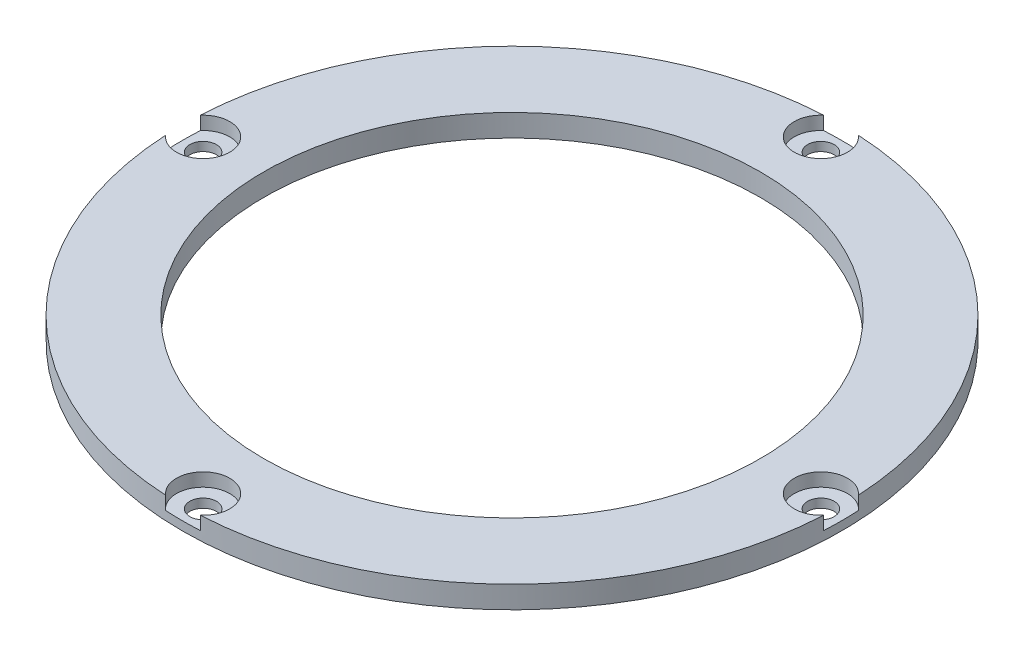
SolidWorks part; units mm, degrees
ref_plane "前视基准面" through (0, 0, 0) normal (0, 0, 1) x (1, 0, 0)
ref_plane "上视基准面" through (0, 0, 0) normal (0, 1, 0) x (1, 0, 0)
ref_plane "右视基准面" through (0, 0, 0) normal (1, 0, 0) x (0, 0, -1)
other "Configuration Table"
sketch "草图1" plane through (0, 0, 0) normal (0, 1, 0) x (1, 0, 0)
  circle A0 centre (0, 0) radius 28
  circle A1 centre (0, 0) radius 37.15
  circle A3 centre (0, 34.825) radius 1.5
  circle A4 centre (-34.825, 0) radius 1.5
  circle A5 centre (0, -34.825) radius 1.5
  circle A6 centre (34.825, 0) radius 1.5
extrude "凸台-拉伸1" add sketch "草图1" along normal blind 3
sketch "草图3" plane through (0, 3, 0) normal (0, 1, 0) x (1, 0, 0)
  circle A0 centre (0, 34.825) radius 3
  circle A1 centre (-34.825, 0) radius 3
  circle A2 centre (0, -34.825) radius 3
  circle A3 centre (34.825, 0) radius 3
extrude "切除-拉伸1" cut sketch "草图3" against normal blind 2
sketch "草图4" plane through (0, 3, 0) normal (0, 1, 0) x (1, 0, 0)
  circle A0 centre (0, 0) radius 37.15
extrude "切除-拉伸2" cut sketch "草图4" against normal blind 0.5
